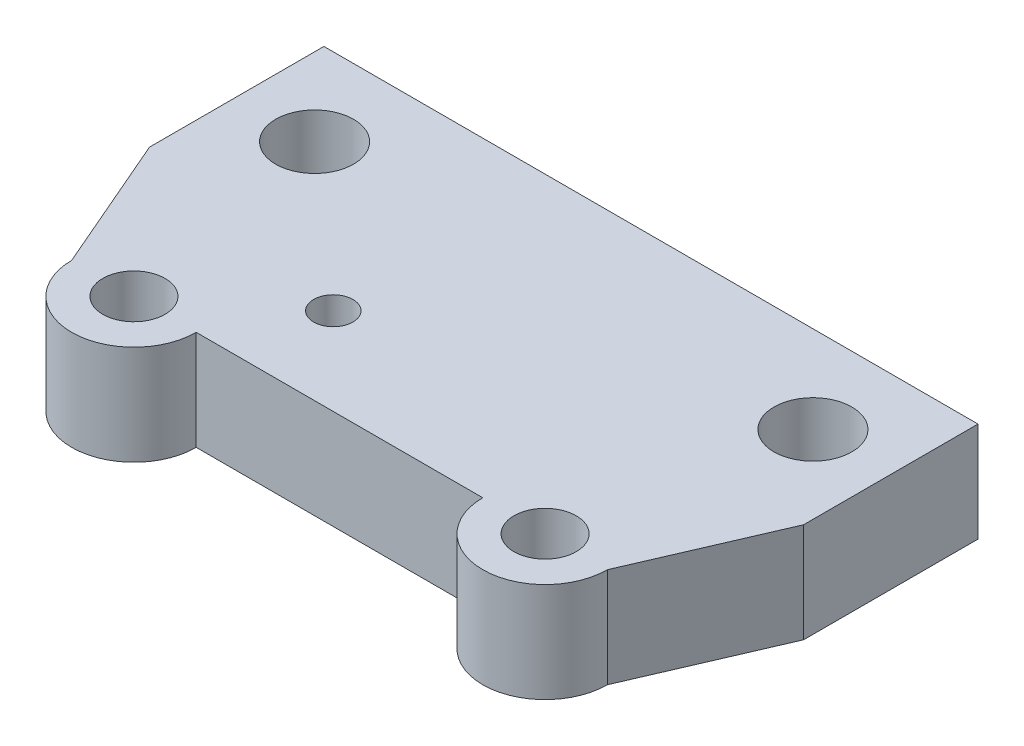
SolidWorks part; units mm, degrees
material "6061-T6 (SS)"
ref_plane "X-Y Datum" through (0, 0, 0) normal (0, 0, 1) x (1, 0, 0)
ref_plane "X-Z Datum" through (0, 0, 0) normal (0, 1, 0) x (1, 0, 0)
ref_plane "Y-Z Datum" through (0, 0, 0) normal (1, 0, 0) x (0, 0, -1)
sketch "Sketch1" plane through (0, 0, 0) normal (0, 1, 0) x (1, 0, 0)
  line L0 (41.91, 0) -> (0, 0) construction
  line L1 (54.2925, 13.97) -> (-12.3825, 13.97) construction
  line L4 (54.2925, 31.75) -> (-12.3825, 31.75)
  line L6 (46.355, 22.86) -> (-4.445, 22.86) construction
  line L7 (54.2925, 31.75) -> (54.2925, 13.97)
  line L8 (-12.3825, 31.75) -> (-12.3825, 13.97)
  line L18 (35.56, 0) -> (6.35, 0)
  line L19 (48.26, 0) -> (54.2925, 13.97)
  line L21 (-6.35, 0) -> (-12.3825, 13.97)
  circle A0 centre (0, 0) radius 3.175
  circle A1 centre (41.91, 0) radius 3.175
  circle A2 centre (46.355, 22.86) radius 3.9688
  circle A3 centre (-4.445, 22.86) radius 3.9687
  arc A4 (48.26, 0) -> (35.56, 0) centre (41.91, 0) cw
  arc A5 (6.35, 0) -> (-6.35, 0) centre (0, 0) cw
  circle A6 centre (11.43, 8.89) radius 2
  point P25 (20.955, 0)
  point P30 (20.955, 31.75)
  dimension "D2" = 6.35
  dimension "D7" = 7.9375
  dimension "D8" = 6.35
  dimension "D12" = 4
  dimension "D10" = 7.9375
  dimension "D3" = 50.8
  dimension "D4" = 17.78
  dimension "D5" = 8.89
  dimension "D6" = 31.75
  dimension "D9" = 41.91
  dimension "D11" = 7.9375
  dimension "D13" = 8.89
  dimension "D14" = 11.43
extrude "Boss-Extrude1" add sketch "Sketch1" against normal blind 10.16
sketch "Sketch3" plane through (0, 0, 0) normal (0, 1, 0) x (1, 0, 0)
  line L0 (0, 0) -> (0, -44.5462) construction
  line L1 (0, 0) -> (26.3151, -45.579) construction
  dimension "D1" = 30
